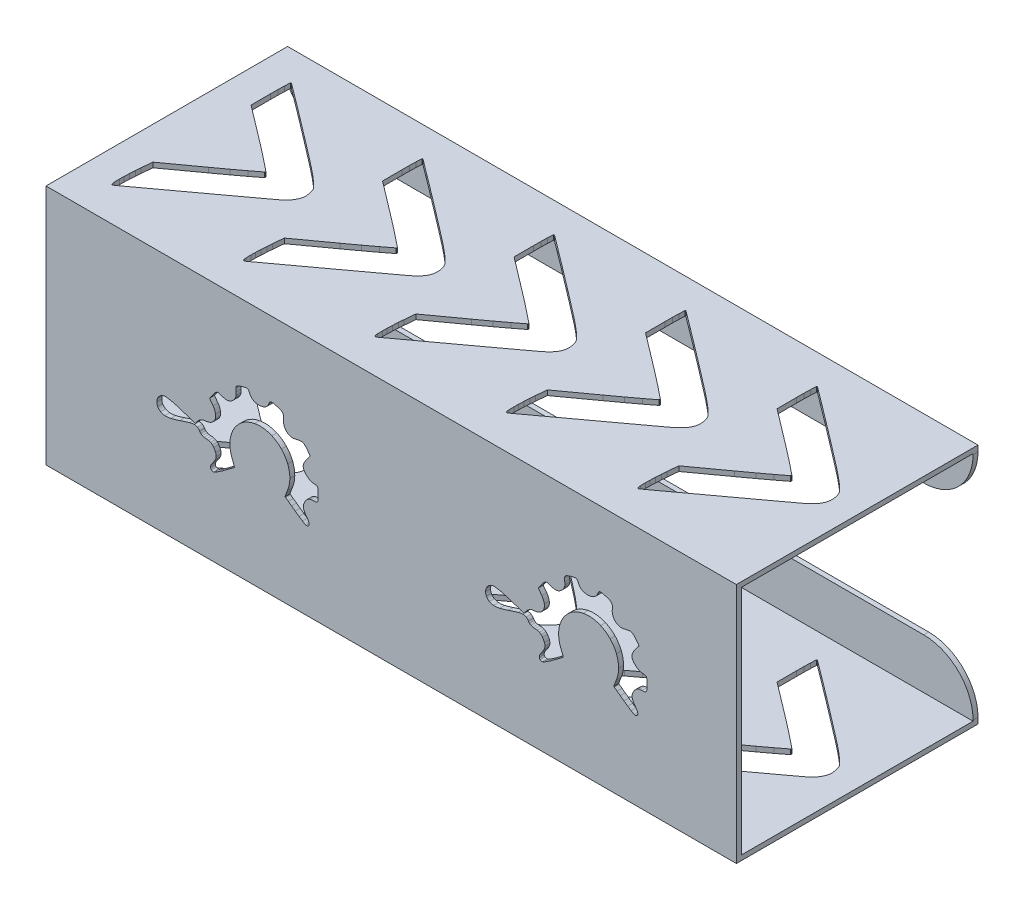
SolidWorks part; units mm, degrees
ref_plane "Front Plane" through (0, 0, 0) normal (1, 0, 0) x (0, 1, 0)
ref_plane "Top Plane" through (0, 0, 0) normal (0, 0, 1) x (0, 1, 0)
ref_plane "Right Plane" through (0, 0, 0) normal (0, 1, 0) x (-1, 0, 0)
sketch "Sketch1" plane through (0, 0, 0) normal (1, 0, 0) x (0, 1, 0)
  line L1 (0, 0) -> (73.5, 0)
  line L2 (0, 0) -> (0, -73.5)
  line L3 (0, -73.5) -> (73.5, -73.5)
  line L4 (73.5, 0) -> (73.5, -73.5)
  dimension "D1" = 73.5
  dimension "D2" = 73.5
extrude "Boss-Extrude1" add sketch "Sketch1" along normal blind 210
shell "Shell1" thickness 1.5
sketch "Sketch2" plane through (0, 0, -73.5) normal (0, 0, -1) x (1, 0, 0)
  line L0 (0, 0) -> (0, -73.5) construction
  line L1 (0, -16.75) -> (210, -16.75)
  line L2 (0, -16.75) -> (0, -56.75)
  line L3 (0, -56.75) -> (210, -56.75)
  line L4 (210, -16.75) -> (210, -56.75)
  line L5 (210, 0) -> (210, -73.5) construction
  line L6 (0, -36.75) -> (210, -36.75) construction
  dimension "D1" = 40
extrude "Cut-Extrude1" cut sketch "Sketch2" against normal up to surface (72 mm away) up to face at (105, 36.75, -1.5)
fillet "Fillet1" radius 15 4 edges at (0, 16.75, -72.75) (0, 56.75, -72.75) (210, 16.75, -72.75) (210, 56.75, -72.75)
sketch "Sketch3" plane through (0, 0, 0) normal (0, -1, 0) x (1, 0, 0)
  line L11 (9.6633, -19.2287) -> (9.9758, -22.537)
  line L12 (9.9758, -22.537) -> (19.7943, -29.6426)
  line L13 (19.7704, -44.9753) -> (9.8778, -52.4962)
  line L14 (9.8778, -52.4962) -> (9.8646, -58.4652)
  line L15 (10.3119, -64.3696) -> (14.8164, -60.9945)
  line L16 (21.2461, -18.6408) -> (10.7313, -10.9162)
  line L31 (49.6633, -19.2287) -> (49.9758, -22.537)
  line L32 (49.9758, -22.537) -> (59.7943, -29.6426)
  line L33 (59.7704, -44.9753) -> (49.8778, -52.4962)
  line L34 (49.8778, -52.4962) -> (49.8646, -58.4652)
  line L35 (50.3119, -64.3696) -> (54.8164, -60.9945)
  line L36 (61.2461, -18.6408) -> (50.7313, -10.9162)
  line L37 (89.6633, -19.2287) -> (89.9758, -22.537)
  line L38 (89.9758, -22.537) -> (99.7943, -29.6426)
  line L39 (99.7704, -44.9753) -> (89.8778, -52.4962)
  line L40 (89.8778, -52.4962) -> (89.8646, -58.4652)
  line L41 (90.3119, -64.3696) -> (94.8164, -60.9945)
  line L42 (101.2461, -18.6408) -> (90.7313, -10.9162)
  line L43 (129.6633, -19.2287) -> (129.9758, -22.537)
  line L44 (129.9758, -22.537) -> (139.7943, -29.6426)
  line L45 (139.7704, -44.9753) -> (129.8778, -52.4962)
  line L46 (129.8778, -52.4962) -> (129.8646, -58.4652)
  line L47 (130.3119, -64.3696) -> (134.8164, -60.9945)
  line L48 (141.2461, -18.6408) -> (130.7313, -10.9162)
  line L49 (169.6633, -19.2287) -> (169.9758, -22.537)
  line L50 (169.9758, -22.537) -> (179.7943, -29.6426)
  line L51 (179.7704, -44.9753) -> (169.8778, -52.4962)
  line L52 (169.8778, -52.4962) -> (169.8646, -58.4652)
  line L53 (170.3119, -64.3696) -> (174.8164, -60.9945)
  line L54 (181.2461, -18.6408) -> (170.7313, -10.9162)
  arc A69 (9.3471, -12.9692) -> (9.3707, -14.3369) centre (51.9904, -12.917) ccw
  arc A70 (9.3707, -14.3369) -> (9.4414, -16.0252) centre (107.7192, -11.0605) ccw
  arc A71 (9.4414, -16.0252) -> (9.5432, -17.7473) centre (110.2692, -10.9318) ccw
  arc A72 (9.5432, -17.7473) -> (9.6633, -19.2287) centre (65.2049, -13.9809) ccw
  arc A73 (23.5603, -32.3922) -> (19.7943, -29.6426) centre (-306.7468, -480.8529) ccw
  arc A74 (26.736, -34.7646) -> (23.5603, -32.3922) centre (-149.6013, -267.4951) ccw
  arc A75 (29.5168, -36.8768) -> (26.736, -34.7646) centre (-846.1457, -1186.7971) ccw
  arc A76 (29.6381, -37.1011) -> (29.5168, -36.8768) centre (29.3291, -37.1233) ccw
  arc A77 (29.5389, -37.3284) -> (29.6381, -37.1011) centre (29.3719, -37.1202) ccw
  arc A78 (26.75, -39.5597) -> (29.5389, -37.3284) centre (-850.317, 1059.5567) ccw
  arc A79 (23.5616, -42.0662) -> (26.75, -39.5597) centre (-147.1808, 178.4052) ccw
  arc A80 (19.7704, -44.9753) -> (23.5616, -42.0662) centre (-304.1542, 381.0974) ccw
  arc A81 (9.8646, -58.4652) -> (9.8787, -60.754) centre (146.6597, -58.7673) ccw
  arc A82 (9.8787, -60.754) -> (9.9336, -62.6808) centre (79.0341, -59.7495) ccw
  arc A83 (9.9336, -62.6808) -> (10.01, -64.3317) centre (222.492, -53.6638) ccw
  arc A84 (10.01, -64.3317) -> (10.1178, -64.4342) centre (10.1178, -64.3263) ccw
  arc A85 (10.1178, -64.4342) -> (10.3119, -64.3696) centre (10.1178, -64.1106) ccw
  arc A86 (14.8164, -60.9945) -> (19.8325, -57.2143) centre (-718.1391, 916.8002) ccw
  arc A87 (19.8325, -57.2143) -> (25.7388, -52.7247) centre (-1410.6569, 1830.8178) ccw
  arc A88 (25.7388, -52.7247) -> (34.2763, -46.1677) centre (-929.7355, 1200.1846) ccw
  arc A89 (34.2763, -46.1677) -> (38.4646, -42.775) centre (-39.0599, 48.6473) ccw
  arc A90 (38.4646, -42.775) -> (40.8424, -40.5892) centre (12.366, -11.9978) ccw
  arc A91 (40.8424, -40.5892) -> (41.7639, -39.1357) centre (38.0891, -37.8248) ccw
  arc A92 (41.7639, -39.1357) -> (42.1636, -37.0187) centre (35.2358, -36.8069) ccw
  arc A93 (42.1636, -37.0187) -> (41.8194, -35.0985) centre (37.4413, -36.8743) ccw
  arc A94 (41.8194, -35.0985) -> (40.6686, -33.2867) centre (36.2813, -37.3449) ccw
  arc A95 (40.6686, -33.2867) -> (38.6605, -31.4846) centre (29.9998, -43.1552) ccw
  arc A96 (38.6605, -31.4846) -> (31.0836, -25.8807) centre (-1705.4642, -2381.7586) ccw
  arc A97 (31.0836, -25.8807) -> (21.2461, -18.6408) centre (-4787.6013, -6563.1202) ccw
  arc A98 (10.7313, -10.9162) -> (9.9784, -10.4092) centre (4.1483, -19.8789) ccw
  arc A99 (9.9784, -10.4092) -> (9.6868, -10.4253) centre (9.8442, -10.6272) ccw
  arc A100 (9.6868, -10.4253) -> (9.4817, -10.7416) centre (10.0409, -10.8795) ccw
  arc A101 (9.4817, -10.7416) -> (9.3727, -11.5193) centre (13.2039, -11.6596) ccw
  arc A102 (9.3727, -11.5193) -> (9.3471, -12.9692) centre (47.6772, -12.9223) ccw
  arc A277 (63.5603, -32.3922) -> (59.7943, -29.6426) centre (-266.7468, -480.8529) ccw
  arc A278 (66.736, -34.7646) -> (63.5603, -32.3922) centre (-109.6013, -267.4951) ccw
  arc A279 (69.5168, -36.8768) -> (66.736, -34.7646) centre (-806.1457, -1186.7971) ccw
  arc A280 (69.6381, -37.1011) -> (69.5168, -36.8768) centre (69.3291, -37.1233) ccw
  arc A281 (69.5389, -37.3284) -> (69.6381, -37.1011) centre (69.3719, -37.1202) ccw
  arc A282 (66.75, -39.5597) -> (69.5389, -37.3284) centre (-810.317, 1059.5567) ccw
  arc A283 (63.5616, -42.0662) -> (66.75, -39.5597) centre (-107.1808, 178.4052) ccw
  arc A284 (59.7704, -44.9753) -> (63.5616, -42.0662) centre (-264.1542, 381.0974) ccw
  arc A285 (49.8646, -58.4652) -> (49.8787, -60.754) centre (186.6597, -58.7673) ccw
  arc A286 (49.8787, -60.754) -> (49.9336, -62.6808) centre (119.0341, -59.7495) ccw
  arc A287 (49.9336, -62.6808) -> (50.01, -64.3317) centre (262.492, -53.6638) ccw
  arc A288 (50.01, -64.3317) -> (50.1178, -64.4342) centre (50.1178, -64.3263) ccw
  arc A289 (50.1178, -64.4342) -> (50.3119, -64.3696) centre (50.1178, -64.1106) ccw
  arc A290 (54.8164, -60.9945) -> (59.8325, -57.2143) centre (-678.1391, 916.8002) ccw
  arc A291 (59.8325, -57.2143) -> (65.7388, -52.7247) centre (-1370.6569, 1830.8178) ccw
  arc A292 (65.7388, -52.7247) -> (74.2763, -46.1677) centre (-889.7355, 1200.1846) ccw
  arc A293 (74.2763, -46.1677) -> (78.4646, -42.775) centre (0.9401, 48.6473) ccw
  arc A294 (78.4646, -42.775) -> (80.8424, -40.5892) centre (52.366, -11.9978) ccw
  arc A295 (80.8424, -40.5892) -> (81.7639, -39.1357) centre (78.0891, -37.8248) ccw
  arc A296 (81.7639, -39.1357) -> (82.1636, -37.0187) centre (75.2358, -36.8069) ccw
  arc A297 (82.1636, -37.0187) -> (81.8194, -35.0985) centre (77.4413, -36.8743) ccw
  arc A298 (81.8194, -35.0985) -> (80.6686, -33.2867) centre (76.2813, -37.3449) ccw
  arc A299 (80.6686, -33.2867) -> (78.6605, -31.4846) centre (69.9998, -43.1552) ccw
  arc A300 (78.6605, -31.4846) -> (71.0836, -25.8807) centre (-1665.4642, -2381.7586) ccw
  arc A301 (71.0836, -25.8807) -> (61.2461, -18.6408) centre (-4747.6013, -6563.1202) ccw
  arc A302 (50.7313, -10.9162) -> (49.9784, -10.4092) centre (44.1483, -19.8789) ccw
  arc A303 (49.9784, -10.4092) -> (49.6868, -10.4253) centre (49.8442, -10.6272) ccw
  arc A304 (49.6868, -10.4253) -> (49.4817, -10.7416) centre (50.0409, -10.8795) ccw
  arc A305 (49.4817, -10.7416) -> (49.3727, -11.5193) centre (53.2039, -11.6596) ccw
  arc A306 (49.3727, -11.5193) -> (49.3471, -12.9692) centre (87.6772, -12.9223) ccw
  arc A307 (49.3471, -12.9692) -> (49.3707, -14.3369) centre (91.9904, -12.917) ccw
  arc A308 (49.3707, -14.3369) -> (49.4414, -16.0252) centre (147.7192, -11.0605) ccw
  arc A309 (49.4414, -16.0252) -> (49.5432, -17.7473) centre (150.2692, -10.9318) ccw
  arc A310 (49.5432, -17.7473) -> (49.6633, -19.2287) centre (105.2049, -13.9809) ccw
  arc A311 (103.5603, -32.3922) -> (99.7943, -29.6426) centre (-226.7468, -480.8529) ccw
  arc A312 (106.736, -34.7646) -> (103.5603, -32.3922) centre (-69.6013, -267.4951) ccw
  arc A313 (109.5168, -36.8768) -> (106.736, -34.7646) centre (-766.1457, -1186.7971) ccw
  arc A314 (109.6381, -37.1011) -> (109.5168, -36.8768) centre (109.3291, -37.1233) ccw
  arc A315 (109.5389, -37.3284) -> (109.6381, -37.1011) centre (109.3719, -37.1202) ccw
  arc A316 (106.75, -39.5597) -> (109.5389, -37.3284) centre (-770.317, 1059.5567) ccw
  arc A317 (103.5616, -42.0662) -> (106.75, -39.5597) centre (-67.1808, 178.4052) ccw
  arc A318 (99.7704, -44.9753) -> (103.5616, -42.0662) centre (-224.1542, 381.0974) ccw
  arc A319 (89.8646, -58.4652) -> (89.8787, -60.754) centre (226.6597, -58.7673) ccw
  arc A320 (89.8787, -60.754) -> (89.9336, -62.6808) centre (159.0341, -59.7495) ccw
  arc A321 (89.9336, -62.6808) -> (90.01, -64.3317) centre (302.492, -53.6638) ccw
  arc A322 (90.01, -64.3317) -> (90.1178, -64.4342) centre (90.1178, -64.3263) ccw
  arc A323 (90.1178, -64.4342) -> (90.3119, -64.3696) centre (90.1178, -64.1106) ccw
  arc A324 (94.8164, -60.9945) -> (99.8325, -57.2143) centre (-638.1391, 916.8002) ccw
  arc A325 (99.8325, -57.2143) -> (105.7388, -52.7247) centre (-1330.6569, 1830.8178) ccw
  arc A326 (105.7388, -52.7247) -> (114.2763, -46.1677) centre (-849.7355, 1200.1846) ccw
  arc A327 (114.2763, -46.1677) -> (118.4646, -42.775) centre (40.9401, 48.6473) ccw
  arc A328 (118.4646, -42.775) -> (120.8424, -40.5892) centre (92.366, -11.9978) ccw
  arc A329 (120.8424, -40.5892) -> (121.7639, -39.1357) centre (118.0891, -37.8248) ccw
  arc A330 (121.7639, -39.1357) -> (122.1636, -37.0187) centre (115.2358, -36.8069) ccw
  arc A331 (122.1636, -37.0187) -> (121.8194, -35.0985) centre (117.4413, -36.8743) ccw
  arc A332 (121.8194, -35.0985) -> (120.6686, -33.2867) centre (116.2813, -37.3449) ccw
  arc A333 (120.6686, -33.2867) -> (118.6605, -31.4846) centre (109.9998, -43.1552) ccw
  arc A334 (118.6605, -31.4846) -> (111.0836, -25.8807) centre (-1625.4642, -2381.7586) ccw
  arc A335 (111.0836, -25.8807) -> (101.2461, -18.6408) centre (-4707.6013, -6563.1202) ccw
  arc A336 (90.7313, -10.9162) -> (89.9784, -10.4092) centre (84.1483, -19.8789) ccw
  arc A337 (89.9784, -10.4092) -> (89.6868, -10.4253) centre (89.8442, -10.6272) ccw
  arc A338 (89.6868, -10.4253) -> (89.4817, -10.7416) centre (90.0409, -10.8795) ccw
  arc A339 (89.4817, -10.7416) -> (89.3727, -11.5193) centre (93.2039, -11.6596) ccw
  arc A340 (89.3727, -11.5193) -> (89.3471, -12.9692) centre (127.6772, -12.9223) ccw
  arc A341 (89.3471, -12.9692) -> (89.3707, -14.3369) centre (131.9904, -12.917) ccw
  arc A342 (89.3707, -14.3369) -> (89.4414, -16.0252) centre (187.7192, -11.0605) ccw
  arc A343 (89.4414, -16.0252) -> (89.5432, -17.7473) centre (190.2692, -10.9318) ccw
  arc A344 (89.5432, -17.7473) -> (89.6633, -19.2287) centre (145.2049, -13.9809) ccw
  arc A345 (143.5603, -32.3922) -> (139.7943, -29.6426) centre (-186.7468, -480.8529) ccw
  arc A346 (146.736, -34.7646) -> (143.5603, -32.3922) centre (-29.6013, -267.4951) ccw
  arc A347 (149.5168, -36.8768) -> (146.736, -34.7646) centre (-726.1457, -1186.7971) ccw
  arc A348 (149.6381, -37.1011) -> (149.5168, -36.8768) centre (149.3291, -37.1233) ccw
  arc A349 (149.5389, -37.3284) -> (149.6381, -37.1011) centre (149.3719, -37.1202) ccw
  arc A350 (146.75, -39.5597) -> (149.5389, -37.3284) centre (-730.317, 1059.5567) ccw
  arc A351 (143.5616, -42.0662) -> (146.75, -39.5597) centre (-27.1808, 178.4052) ccw
  arc A352 (139.7704, -44.9753) -> (143.5616, -42.0662) centre (-184.1542, 381.0974) ccw
  arc A353 (129.8646, -58.4652) -> (129.8787, -60.754) centre (266.6597, -58.7673) ccw
  arc A354 (129.8787, -60.754) -> (129.9336, -62.6808) centre (199.0341, -59.7495) ccw
  arc A355 (129.9336, -62.6808) -> (130.01, -64.3317) centre (342.492, -53.6638) ccw
  arc A356 (130.01, -64.3317) -> (130.1178, -64.4342) centre (130.1178, -64.3263) ccw
  arc A357 (130.1178, -64.4342) -> (130.3119, -64.3696) centre (130.1178, -64.1106) ccw
  arc A358 (134.8164, -60.9945) -> (139.8325, -57.2143) centre (-598.1391, 916.8002) ccw
  arc A359 (139.8325, -57.2143) -> (145.7388, -52.7247) centre (-1290.6569, 1830.8178) ccw
  arc A360 (145.7388, -52.7247) -> (154.2763, -46.1677) centre (-809.7355, 1200.1846) ccw
  arc A361 (154.2763, -46.1677) -> (158.4646, -42.775) centre (80.9401, 48.6473) ccw
  arc A362 (158.4646, -42.775) -> (160.8424, -40.5892) centre (132.366, -11.9978) ccw
  arc A363 (160.8424, -40.5892) -> (161.7639, -39.1357) centre (158.0891, -37.8248) ccw
  arc A364 (161.7639, -39.1357) -> (162.1636, -37.0187) centre (155.2358, -36.8069) ccw
  arc A365 (162.1636, -37.0187) -> (161.8194, -35.0985) centre (157.4413, -36.8743) ccw
  arc A366 (161.8194, -35.0985) -> (160.6686, -33.2867) centre (156.2813, -37.3449) ccw
  arc A367 (160.6686, -33.2867) -> (158.6605, -31.4846) centre (149.9998, -43.1552) ccw
  arc A368 (158.6605, -31.4846) -> (151.0836, -25.8807) centre (-1585.4642, -2381.7586) ccw
  arc A369 (151.0836, -25.8807) -> (141.2461, -18.6408) centre (-4667.6013, -6563.1202) ccw
  arc A370 (130.7313, -10.9162) -> (129.9784, -10.4092) centre (124.1483, -19.8789) ccw
  arc A371 (129.9784, -10.4092) -> (129.6868, -10.4253) centre (129.8442, -10.6272) ccw
  arc A372 (129.6868, -10.4253) -> (129.4817, -10.7416) centre (130.0409, -10.8795) ccw
  arc A373 (129.4817, -10.7416) -> (129.3727, -11.5193) centre (133.2039, -11.6596) ccw
  arc A374 (129.3727, -11.5193) -> (129.3471, -12.9692) centre (167.6772, -12.9223) ccw
  arc A375 (129.3471, -12.9692) -> (129.3707, -14.3369) centre (171.9904, -12.917) ccw
  arc A376 (129.3707, -14.3369) -> (129.4414, -16.0252) centre (227.7192, -11.0605) ccw
  arc A377 (129.4414, -16.0252) -> (129.5432, -17.7473) centre (230.2692, -10.9318) ccw
  arc A378 (129.5432, -17.7473) -> (129.6633, -19.2287) centre (185.2049, -13.9809) ccw
  arc A379 (183.5603, -32.3922) -> (179.7943, -29.6426) centre (-146.7468, -480.8529) ccw
  arc A380 (186.736, -34.7646) -> (183.5603, -32.3922) centre (10.3987, -267.4951) ccw
  arc A381 (189.5168, -36.8768) -> (186.736, -34.7646) centre (-686.1457, -1186.7971) ccw
  arc A382 (189.6381, -37.1011) -> (189.5168, -36.8768) centre (189.3291, -37.1233) ccw
  arc A383 (189.5389, -37.3284) -> (189.6381, -37.1011) centre (189.3719, -37.1202) ccw
  arc A384 (186.75, -39.5597) -> (189.5389, -37.3284) centre (-690.317, 1059.5567) ccw
  arc A385 (183.5616, -42.0662) -> (186.75, -39.5597) centre (12.8192, 178.4052) ccw
  arc A386 (179.7704, -44.9753) -> (183.5616, -42.0662) centre (-144.1542, 381.0974) ccw
  arc A387 (169.8646, -58.4652) -> (169.8787, -60.754) centre (306.6597, -58.7673) ccw
  arc A388 (169.8787, -60.754) -> (169.9336, -62.6808) centre (239.0341, -59.7495) ccw
  arc A389 (169.9336, -62.6808) -> (170.01, -64.3317) centre (382.492, -53.6638) ccw
  arc A390 (170.01, -64.3317) -> (170.1178, -64.4342) centre (170.1178, -64.3263) ccw
  arc A391 (170.1178, -64.4342) -> (170.3119, -64.3696) centre (170.1178, -64.1106) ccw
  arc A392 (174.8164, -60.9945) -> (179.8325, -57.2143) centre (-558.1391, 916.8002) ccw
  arc A393 (179.8325, -57.2143) -> (185.7388, -52.7247) centre (-1250.6569, 1830.8178) ccw
  arc A394 (185.7388, -52.7247) -> (194.2763, -46.1677) centre (-769.7355, 1200.1846) ccw
  arc A395 (194.2763, -46.1677) -> (198.4646, -42.775) centre (120.9401, 48.6473) ccw
  arc A396 (198.4646, -42.775) -> (200.8424, -40.5892) centre (172.366, -11.9978) ccw
  arc A397 (200.8424, -40.5892) -> (201.7639, -39.1357) centre (198.0891, -37.8248) ccw
  arc A398 (201.7639, -39.1357) -> (202.1636, -37.0187) centre (195.2358, -36.8069) ccw
  arc A399 (202.1636, -37.0187) -> (201.8194, -35.0985) centre (197.4413, -36.8743) ccw
  arc A400 (201.8194, -35.0985) -> (200.6686, -33.2867) centre (196.2813, -37.3449) ccw
  arc A401 (200.6686, -33.2867) -> (198.6605, -31.4846) centre (189.9998, -43.1552) ccw
  arc A402 (198.6605, -31.4846) -> (191.0836, -25.8807) centre (-1545.4642, -2381.7586) ccw
  arc A403 (191.0836, -25.8807) -> (181.2461, -18.6408) centre (-4627.6013, -6563.1202) ccw
  arc A404 (170.7313, -10.9162) -> (169.9784, -10.4092) centre (164.1483, -19.8789) ccw
  arc A405 (169.9784, -10.4092) -> (169.6868, -10.4253) centre (169.8442, -10.6272) ccw
  arc A406 (169.6868, -10.4253) -> (169.4817, -10.7416) centre (170.0409, -10.8795) ccw
  arc A407 (169.4817, -10.7416) -> (169.3727, -11.5193) centre (173.2039, -11.6596) ccw
  arc A408 (169.3727, -11.5193) -> (169.3471, -12.9692) centre (207.6772, -12.9223) ccw
  arc A409 (169.3471, -12.9692) -> (169.3707, -14.3369) centre (211.9904, -12.917) ccw
  arc A410 (169.3707, -14.3369) -> (169.4414, -16.0252) centre (267.7192, -11.0605) ccw
  arc A411 (169.4414, -16.0252) -> (169.5432, -17.7473) centre (270.2692, -10.9318) ccw
  arc A412 (169.5432, -17.7473) -> (169.6633, -19.2287) centre (225.2049, -13.9809) ccw
  dimension "D1" = 5
extrude "Cut-Extrude2" cut sketch "Sketch3" against normal through all
sketch "Sketch7" plane through (0, 0, 0) normal (0, 0, 1) x (-1, 0, 0)
  line L55 (-179.3217, -41.1409) -> (-180.4065, -42.52)
  line L56 (-180.4065, -42.52) -> (-179.3772, -43.8764)
  line L57 (-150.8373, -44.0084) -> (-149.7387, -42.4655)
  line L58 (-149.7387, -42.4655) -> (-150.8112, -41.0148)
  line L59 (-146.277, -34.7471) -> (-145.3963, -33.6595)
  line L60 (-145.3963, -33.6595) -> (-141.2197, -35.0505)
  line L61 (-154.3079, -25.7512) -> (-155.4129, -26.5732)
  line L62 (-155.4129, -26.5732) -> (-156.3598, -27.2767)
  line L63 (-156.3598, -27.2767) -> (-157.1862, -27.8902)
  line L64 (-172.8725, -27.8886) -> (-173.7152, -27.2751)
  line L65 (-173.7152, -27.2751) -> (-174.6812, -26.5717)
  line L66 (-174.6812, -26.5717) -> (-175.8021, -25.7552)
  line L67 (-79.3217, -41.1409) -> (-80.4065, -42.52)
  line L68 (-80.4065, -42.52) -> (-79.3772, -43.8764)
  line L69 (-50.8373, -44.0084) -> (-49.7387, -42.4655)
  line L70 (-49.7387, -42.4655) -> (-50.8112, -41.0148)
  line L71 (-46.277, -34.7471) -> (-45.3963, -33.6595)
  line L72 (-45.3963, -33.6595) -> (-41.2197, -35.0505)
  line L73 (-54.3079, -25.7512) -> (-55.4129, -26.5732)
  line L74 (-55.4129, -26.5732) -> (-56.3598, -27.2767)
  line L75 (-56.3598, -27.2767) -> (-57.1862, -27.8902)
  line L76 (-72.8725, -27.8886) -> (-73.7152, -27.2751)
  line L77 (-73.7152, -27.2751) -> (-74.6812, -26.5717)
  line L78 (-74.6812, -26.5717) -> (-75.8021, -25.7552)
  arc A413 (-180.4257, -36.0856) -> (-181.5388, -35.8347) centre (-181.5388, -38.4304) ccw
  arc A414 (-179.3274, -36.8188) -> (-180.4257, -36.0856) centre (-182.3795, -40.2013) ccw
  arc A415 (-178.5138, -37.8098) -> (-179.3274, -36.8188) centre (-182.215, -40.0189) ccw
  arc A416 (-178.2368, -38.8142) -> (-178.5138, -37.8098) centre (-180.1966, -38.8142) ccw
  arc A417 (-178.3109, -39.2731) -> (-178.2368, -38.8142) centre (-179.6946, -38.8142) ccw
  arc A418 (-178.5555, -39.8885) -> (-178.3109, -39.2731) centre (-183.7292, -37.4762) ccw
  arc A419 (-178.9065, -40.5433) -> (-178.5555, -39.8885) centre (-184.5938, -37.0731) ccw
  arc A420 (-179.3217, -41.1409) -> (-178.9065, -40.5433) centre (-184.1447, -37.3471) ccw
  arc A421 (-179.3772, -43.8764) -> (-178.6531, -44.693) centre (-173.6749, -39.5492) ccw
  arc A422 (-178.6531, -44.693) -> (-178.0494, -45.016) centre (-177.785, -43.7959) ccw
  arc A423 (-178.0494, -45.016) -> (-177.2478, -45.0303) centre (-177.6125, -43.0006) ccw
  arc A424 (-177.2478, -45.0303) -> (-175.6195, -44.691) centre (-182.5834, -15.3439) ccw
  arc A425 (-174.2898, -44.7381) -> (-175.6195, -44.691) centre (-175.0402, -47.1324) ccw
  arc A426 (-173.1167, -45.455) -> (-174.2898, -44.7381) centre (-175.138, -47.4442) ccw
  arc A427 (-172.379, -46.6738) -> (-173.1167, -45.455) centre (-175.3138, -47.6173) ccw
  arc A428 (-172.2605, -48.1041) -> (-172.379, -46.6738) centre (-175.3964, -47.6439) ccw
  arc A429 (-172.2605, -48.1041) -> (-172.2619, -49.1259) centre (-168.7481, -48.6196) ccw
  arc A430 (-172.2619, -49.1259) -> (-171.9159, -49.8005) centre (-171.1069, -48.9595) ccw
  arc A431 (-171.9159, -49.8005) -> (-171.1097, -50.2905) centre (-170.4165, -48.2418) ccw
  arc A432 (-171.1097, -50.2905) -> (-169.5084, -50.7515) centre (-165.2962, -33.1087) ccw
  arc A433 (-169.5084, -50.7515) -> (-168.7977, -50.8707) centre (-168.2786, -45.6007) ccw
  arc A434 (-168.7977, -50.8707) -> (-168.3518, -50.8022) centre (-168.7086, -49.9654) ccw
  arc A435 (-168.3518, -50.8022) -> (-168.0469, -50.5394) centre (-168.6118, -50.1925) ccw
  arc A436 (-168.0469, -50.5394) -> (-167.8133, -50.0288) centre (-170.0166, -49.3295) ccw
  arc A437 (-166.7743, -48.703) -> (-167.8133, -50.0288) centre (-165.5186, -50.7571) ccw
  arc A438 (-164.9464, -48.1479) -> (-166.7743, -48.703) centre (-164.7908, -51.9476) ccw
  arc A439 (-163.0945, -48.5539) -> (-164.9464, -48.1479) centre (-164.7937, -51.878) ccw
  arc A440 (-161.9863, -49.7902) -> (-163.0945, -48.5539) centre (-164.1462, -50.6114) ccw
  arc A441 (-161.9863, -49.7902) -> (-161.6713, -50.4494) centre (-157.8447, -48.2156) ccw
  arc A442 (-161.6713, -50.4494) -> (-161.3391, -50.7344) centre (-161.0936, -50.1121) ccw
  arc A443 (-161.3391, -50.7344) -> (-160.8627, -50.7816) centre (-161.0178, -49.92) ccw
  arc A444 (-160.8627, -50.7816) -> (-159.9889, -50.5782) centre (-162.4341, -42.0521) ccw
  arc A445 (-159.9889, -50.5782) -> (-158.5462, -50.1113) centre (-166.1882, -28.9623) ccw
  arc A446 (-158.5462, -50.1113) -> (-157.9553, -49.7098) centre (-159.0368, -48.7538) ccw
  arc A447 (-157.9553, -49.7098) -> (-157.7327, -49.1396) centre (-158.6211, -49.1212) ccw
  arc A448 (-157.7327, -49.1396) -> (-157.7978, -48.0994) centre (-164.0024, -49.01) ccw
  arc A449 (-157.8333, -47.3478) -> (-157.7978, -48.0994) centre (-154.0114, -47.5437) ccw
  arc A450 (-157.7066, -46.6918) -> (-157.8333, -47.3478) centre (-155.437, -47.4706) ccw
  arc A451 (-157.4011, -46.0867) -> (-157.7066, -46.6918) centre (-155.3587, -47.4975) ccw
  arc A452 (-156.9014, -45.4873) -> (-157.4011, -46.0867) centre (-153.847, -48.5417) ccw
  arc A453 (-156.0692, -44.8679) -> (-156.9014, -45.4873) centre (-154.3732, -48.0155) ccw
  arc A454 (-155.1947, -44.6147) -> (-156.0692, -44.8679) centre (-155.0448, -46.7691) ccw
  arc A455 (-154.1488, -44.7194) -> (-155.1947, -44.6147) centre (-154.9781, -47.7269) ccw
  arc A456 (-152.7674, -45.1997) -> (-154.1488, -44.7194) centre (-157.1187, -55.4896) ccw
  arc A457 (-152.7674, -45.1997) -> (-152.3251, -45.2609) centre (-152.4323, -44.4073) ccw
  arc A458 (-152.3251, -45.2609) -> (-151.8725, -45.1013) centre (-152.4659, -44.1399) ccw
  arc A459 (-151.8725, -45.1013) -> (-151.3863, -44.6946) centre (-153.0359, -43.2165) ccw
  arc A460 (-151.3863, -44.6946) -> (-150.8373, -44.0084) centre (-157.24, -39.4493) ccw
  arc A461 (-151.5774, -39.2295) -> (-150.8112, -41.0148) centre (-147.4025, -38.4947) ccw
  arc A462 (-151.3315, -37.5125) -> (-151.5774, -39.2295) centre (-148.8331, -38.7465) ccw
  arc A463 (-150.1213, -36.285) -> (-151.3315, -37.5125) centre (-148.8717, -38.7274) ccw
  arc A464 (-148.2526, -35.8347) -> (-150.1213, -36.285) centre (-148.2526, -39.9373) ccw
  arc A465 (-148.2526, -35.8347) -> (-147.7692, -35.7559) centre (-148.2526, -34.3137) ccw
  arc A466 (-147.7692, -35.7559) -> (-147.2206, -35.5153) centre (-148.8296, -32.5924) ccw
  arc A467 (-147.2206, -35.5153) -> (-146.6949, -35.1633) centre (-148.983, -32.3138) ccw
  arc A468 (-146.6949, -35.1633) -> (-146.277, -34.7471) centre (-148.4272, -33.006) ccw
  arc A469 (-141.2197, -35.0505) -> (-139.4009, -35.6076) centre (-128.8343, 2.1394) ccw
  arc A470 (-139.4009, -35.6076) -> (-137.8243, -35.9831) centre (-133.808, -15.6282) ccw
  arc A471 (-137.8243, -35.9831) -> (-136.553, -36.1774) centre (-134.9422, -21.3766) ccw
  arc A472 (-136.553, -36.1774) -> (-135.7787, -36.1241) centre (-136.3147, -33.9882) ccw
  arc A473 (-135.7787, -36.1241) -> (-134.7274, -35.588) centre (-136.4206, -33.5666) ccw
  arc A474 (-134.7274, -35.588) -> (-133.9847, -34.6356) centre (-136.5773, -33.3795) ccw
  arc A475 (-133.9847, -34.6356) -> (-133.7118, -33.4879) centre (-136.4423, -33.4449) ccw
  arc A476 (-133.7118, -33.4879) -> (-133.9752, -32.4014) centre (-135.9396, -33.4528) ccw
  arc A477 (-133.9752, -32.4014) -> (-134.8598, -31.477) centre (-136.0749, -33.5252) ccw
  arc A478 (-134.8598, -31.477) -> (-136.1395, -31.0877) centre (-136.2945, -33.8954) ccw
  arc A479 (-136.1395, -31.0877) -> (-137.9879, -31.2557) centre (-136.4917, -37.4658) ccw
  arc A480 (-137.9879, -31.2557) -> (-140.6662, -32.032) centre (-130.841, -60.9193) ccw
  arc A481 (-143.6014, -32.9683) -> (-140.6662, -32.032) centre (-166.6963, 44.4995) ccw
  arc A482 (-145.1237, -33.2221) -> (-143.6014, -32.9683) centre (-145.3757, -27.0167) ccw
  arc A483 (-146.0607, -32.9871) -> (-145.1237, -33.2221) centre (-145.1931, -31.5133) ccw
  arc A484 (-146.7408, -32.2787) -> (-146.0607, -32.9871) centre (-145.1391, -31.4215) ccw
  arc A485 (-146.7408, -32.2787) -> (-147.0704, -31.8445) centre (-148.2704, -33.0974) ccw
  arc A486 (-147.0704, -31.8445) -> (-147.5245, -31.5238) centre (-148.3653, -33.1964) ccw
  arc A487 (-147.5245, -31.5238) -> (-148.0938, -31.3283) centre (-148.5285, -33.5212) ccw
  arc A488 (-148.0938, -31.3283) -> (-148.7619, -31.2627) centre (-148.7619, -34.698) ccw
  arc A489 (-149.443, -31.1889) -> (-148.7619, -31.2627) centre (-148.7619, -28.0869) ccw
  arc A490 (-150.0616, -30.9707) -> (-149.443, -31.1889) centre (-148.869, -28.5749) ccw
  arc A491 (-150.5963, -30.6145) -> (-150.0616, -30.9707) centre (-148.9217, -28.6807) ccw
  arc A492 (-151.03, -30.1337) -> (-150.5963, -30.6145) centre (-148.8695, -28.6204) ccw
  arc A493 (-151.614, -29.0568) -> (-151.03, -30.1337) centre (-146.624, -27.0476) ccw
  arc A494 (-151.7688, -28.0984) -> (-151.614, -29.0568) centre (-149.5742, -28.2355) ccw
  arc A495 (-151.4982, -27.1265) -> (-151.7688, -28.0984) centre (-149.3442, -28.2499) ccw
  arc A496 (-150.7718, -26.0022) -> (-151.4982, -27.1265) centre (-145.1006, -30.4631) ccw
  arc A497 (-150.7718, -26.0022) -> (-150.1964, -25.0917) centre (-154.8924, -22.7609) ccw
  arc A498 (-150.1964, -25.0917) -> (-150.0425, -24.3322) centre (-151.5425, -24.4236) ccw
  arc A499 (-150.0425, -24.3322) -> (-150.3109, -23.8405) centre (-150.7004, -24.3723) ccw
  arc A500 (-150.3109, -23.8405) -> (-150.9156, -23.6427) centre (-150.9156, -24.6661) ccw
  arc A501 (-150.9156, -23.6427) -> (-151.2597, -23.7345) centre (-150.9156, -24.3335) ccw
  arc A502 (-151.2597, -23.7345) -> (-152.1446, -24.2636) centre (-136.5488, -49.3448) ccw
  arc A503 (-152.1446, -24.2636) -> (-153.186, -24.9467) centre (-138.574, -46.0878) ccw
  arc A504 (-153.186, -24.9467) -> (-154.3079, -25.7512) centre (-130.6122, -57.6073) ccw
  arc A505 (-157.2885, -27.9643) -> (-157.1862, -27.8902) centre (-160.4083, -23.549) ccw
  arc A506 (-157.2885, -27.9643) -> (-157.3198, -28.0554) centre (-157.2409, -28.0316) ccw
  arc A507 (-157.3198, -28.0554) -> (-157.1571, -28.5714) centre (-135.3012, -21.3959) ccw
  arc A508 (-157.1571, -28.5714) -> (-156.9385, -29.1864) centre (-144.3788, -24.3761) ccw
  arc A509 (-156.9385, -29.1864) -> (-156.6535, -29.8984) centre (-133.0805, -20.049) ccw
  arc A510 (-156.1101, -35.2903) -> (-156.6535, -29.8984) centre (-165.2433, -33.4875) ccw
  arc A511 (-158.6575, -40.0916) -> (-156.1101, -35.2903) centre (-165.3437, -33.4677) ccw
  arc A512 (-163.398, -42.6364) -> (-158.6575, -40.0916) centre (-165.1792, -33.6306) ccw
  arc A513 (-168.6907, -42.0486) -> (-163.398, -42.6364) centre (-165.1136, -33.962) ccw
  arc A514 (-171.5993, -40.0109) -> (-168.6907, -42.0486) centre (-164.9768, -33.6526) ccw
  arc A515 (-173.5226, -37.0187) -> (-171.5993, -40.0109) centre (-164.9367, -33.6141) ccw
  arc A516 (-174.1746, -33.5171) -> (-173.5226, -37.0187) centre (-164.9102, -33.6036) ccw
  arc A517 (-173.4578, -30.0268) -> (-174.1746, -33.5171) centre (-164.8968, -33.6038) ccw
  arc A518 (-173.4578, -30.0268) -> (-173.1522, -29.2654) centre (-200.3598, -18.7864) ccw
  arc A519 (-173.1522, -29.2654) -> (-172.9163, -28.6088) centre (-187.4446, -23.7607) ccw
  arc A520 (-172.9163, -28.6088) -> (-172.7381, -28.0556) centre (-199.3716, -19.7807) ccw
  arc A521 (-172.7381, -28.0556) -> (-172.7691, -27.9632) centre (-172.8176, -28.0309) ccw
  arc A522 (-172.8725, -27.8886) -> (-172.7691, -27.9632) centre (-163.9954, -15.694) ccw
  arc A523 (-175.8021, -25.7552) -> (-176.9492, -24.9459) centre (-202.9107, -62.9619) ccw
  arc A524 (-176.9492, -24.9459) -> (-177.9966, -24.2633) centre (-193.3079, -48.9003) ccw
  arc A525 (-177.9966, -24.2633) -> (-178.8866, -23.7277) centre (-197.118, -55.0309) ccw
  arc A526 (-178.8866, -23.7277) -> (-179.2011, -23.6427) centre (-179.2011, -24.2678) ccw
  arc A527 (-179.2011, -23.6427) -> (-179.7692, -23.8455) centre (-179.2011, -24.54) ccw
  arc A528 (-179.7692, -23.8455) -> (-180.0158, -24.3425) centre (-179.3429, -24.3666) ccw
  arc A529 (-180.0158, -24.3425) -> (-179.8518, -25.1053) centre (-178.4252, -24.3996) ccw
  arc A530 (-179.8518, -25.1053) -> (-179.2858, -26.0022) centre (-175.2544, -22.8311) ccw
  arc A531 (-178.5594, -27.1265) -> (-179.2858, -26.0022) centre (-184.957, -30.4631) ccw
  arc A532 (-178.2888, -28.0984) -> (-178.5594, -27.1265) centre (-180.7135, -28.2499) ccw
  arc A533 (-178.4436, -29.0568) -> (-178.2888, -28.0984) centre (-180.4834, -28.2355) ccw
  arc A534 (-179.0276, -30.1337) -> (-178.4436, -29.0568) centre (-183.4336, -27.0476) ccw
  arc A535 (-179.4636, -30.6169) -> (-179.0276, -30.1337) centre (-181.1985, -28.6132) ccw
  arc A536 (-179.9994, -30.9727) -> (-179.4636, -30.6169) centre (-181.1199, -28.7039) ccw
  arc A537 (-180.622, -31.1894) -> (-179.9994, -30.9727) centre (-181.182, -28.5783) ccw
  arc A538 (-181.3136, -31.2627) -> (-180.622, -31.1894) centre (-181.3136, -27.9644) ccw
  arc A539 (-181.3136, -31.2627) -> (-182.2055, -31.3308) centre (-181.3136, -37.1429) ccw
  arc A540 (-182.2055, -31.3308) -> (-182.5988, -31.5839) centre (-182.1184, -31.8981) ccw
  arc A541 (-182.5988, -31.5839) -> (-182.7741, -32.1238) centre (-181.6926, -32.1766) ccw
  arc A542 (-182.7741, -32.1238) -> (-182.8088, -33.5487) centre (-153.57, -33.5488) ccw
  arc A543 (-182.8088, -33.5487) -> (-182.7742, -34.9101) centre (-155.9949, -33.5488) ccw
  arc A544 (-182.7742, -34.9101) -> (-182.6113, -35.4791) centre (-181.4675, -34.8437) ccw
  arc A545 (-182.6113, -35.4791) -> (-182.2535, -35.7506) centre (-182.124, -35.2084) ccw
  arc A546 (-182.2535, -35.7506) -> (-181.5388, -35.8347) centre (-181.5388, -32.7576) ccw
  arc A547 (-79.3772, -43.8764) -> (-78.6531, -44.693) centre (-73.6749, -39.5492) ccw
  arc A548 (-78.6531, -44.693) -> (-78.0494, -45.016) centre (-77.785, -43.7959) ccw
  arc A549 (-78.0494, -45.016) -> (-77.2478, -45.0303) centre (-77.6125, -43.0006) ccw
  arc A550 (-77.2478, -45.0303) -> (-75.6195, -44.691) centre (-82.5834, -15.3439) ccw
  arc A551 (-74.2898, -44.7381) -> (-75.6195, -44.691) centre (-75.0402, -47.1324) ccw
  arc A552 (-73.1167, -45.455) -> (-74.2898, -44.7381) centre (-75.138, -47.4442) ccw
  arc A553 (-72.379, -46.6738) -> (-73.1167, -45.455) centre (-75.3138, -47.6173) ccw
  arc A554 (-72.2605, -48.1041) -> (-72.379, -46.6738) centre (-75.3964, -47.6439) ccw
  arc A555 (-72.2605, -48.1041) -> (-72.2619, -49.1259) centre (-68.7481, -48.6196) ccw
  arc A556 (-72.2619, -49.1259) -> (-71.9159, -49.8005) centre (-71.1069, -48.9595) ccw
  arc A557 (-71.9159, -49.8005) -> (-71.1097, -50.2905) centre (-70.4165, -48.2418) ccw
  arc A558 (-71.1097, -50.2905) -> (-69.5084, -50.7515) centre (-65.2962, -33.1087) ccw
  arc A559 (-69.5084, -50.7515) -> (-68.7977, -50.8707) centre (-68.2786, -45.6007) ccw
  arc A560 (-68.7977, -50.8707) -> (-68.3518, -50.8022) centre (-68.7086, -49.9654) ccw
  arc A561 (-68.3518, -50.8022) -> (-68.0469, -50.5394) centre (-68.6118, -50.1925) ccw
  arc A562 (-68.0469, -50.5394) -> (-67.8133, -50.0288) centre (-70.0166, -49.3295) ccw
  arc A563 (-66.7743, -48.703) -> (-67.8133, -50.0288) centre (-65.5186, -50.7571) ccw
  arc A564 (-64.9464, -48.1479) -> (-66.7743, -48.703) centre (-64.7908, -51.9476) ccw
  arc A565 (-63.0945, -48.5539) -> (-64.9464, -48.1479) centre (-64.7937, -51.878) ccw
  arc A566 (-61.9863, -49.7902) -> (-63.0945, -48.5539) centre (-64.1462, -50.6114) ccw
  arc A567 (-61.9863, -49.7902) -> (-61.6713, -50.4494) centre (-57.8447, -48.2156) ccw
  arc A568 (-61.6713, -50.4494) -> (-61.3391, -50.7344) centre (-61.0936, -50.1121) ccw
  arc A569 (-61.3391, -50.7344) -> (-60.8627, -50.7816) centre (-61.0178, -49.92) ccw
  arc A570 (-60.8627, -50.7816) -> (-59.9889, -50.5782) centre (-62.4341, -42.0521) ccw
  arc A571 (-59.9889, -50.5782) -> (-58.5462, -50.1113) centre (-66.1882, -28.9623) ccw
  arc A572 (-58.5462, -50.1113) -> (-57.9553, -49.7098) centre (-59.0368, -48.7538) ccw
  arc A573 (-57.9553, -49.7098) -> (-57.7327, -49.1396) centre (-58.6211, -49.1212) ccw
  arc A574 (-57.7327, -49.1396) -> (-57.7978, -48.0994) centre (-64.0024, -49.01) ccw
  arc A575 (-57.8333, -47.3478) -> (-57.7978, -48.0994) centre (-54.0114, -47.5437) ccw
  arc A576 (-57.7066, -46.6918) -> (-57.8333, -47.3478) centre (-55.437, -47.4706) ccw
  arc A577 (-57.4011, -46.0867) -> (-57.7066, -46.6918) centre (-55.3587, -47.4975) ccw
  arc A578 (-56.9014, -45.4873) -> (-57.4011, -46.0867) centre (-53.847, -48.5417) ccw
  arc A579 (-56.0692, -44.8679) -> (-56.9014, -45.4873) centre (-54.3732, -48.0155) ccw
  arc A580 (-55.1947, -44.6147) -> (-56.0692, -44.8679) centre (-55.0448, -46.7691) ccw
  arc A581 (-54.1488, -44.7194) -> (-55.1947, -44.6147) centre (-54.9781, -47.7269) ccw
  arc A582 (-52.7674, -45.1997) -> (-54.1488, -44.7194) centre (-57.1187, -55.4896) ccw
  arc A583 (-52.7674, -45.1997) -> (-52.3251, -45.2609) centre (-52.4323, -44.4073) ccw
  arc A584 (-52.3251, -45.2609) -> (-51.8725, -45.1013) centre (-52.4659, -44.1399) ccw
  arc A585 (-51.8725, -45.1013) -> (-51.3863, -44.6946) centre (-53.0359, -43.2165) ccw
  arc A586 (-51.3863, -44.6946) -> (-50.8373, -44.0084) centre (-57.24, -39.4493) ccw
  arc A587 (-51.5774, -39.2295) -> (-50.8112, -41.0148) centre (-47.4025, -38.4947) ccw
  arc A588 (-51.3315, -37.5125) -> (-51.5774, -39.2295) centre (-48.8331, -38.7465) ccw
  arc A589 (-50.1213, -36.285) -> (-51.3315, -37.5125) centre (-48.8717, -38.7274) ccw
  arc A590 (-48.2526, -35.8347) -> (-50.1213, -36.285) centre (-48.2526, -39.9373) ccw
  arc A591 (-48.2526, -35.8347) -> (-47.7692, -35.7559) centre (-48.2526, -34.3137) ccw
  arc A592 (-47.7692, -35.7559) -> (-47.2206, -35.5153) centre (-48.8296, -32.5924) ccw
  arc A593 (-47.2206, -35.5153) -> (-46.6949, -35.1633) centre (-48.983, -32.3138) ccw
  arc A594 (-46.6949, -35.1633) -> (-46.277, -34.7471) centre (-48.4272, -33.006) ccw
  arc A595 (-41.2197, -35.0505) -> (-39.4009, -35.6076) centre (-28.8343, 2.1394) ccw
  arc A596 (-39.4009, -35.6076) -> (-37.8243, -35.9831) centre (-33.808, -15.6282) ccw
  arc A597 (-37.8243, -35.9831) -> (-36.553, -36.1774) centre (-34.9422, -21.3766) ccw
  arc A598 (-36.553, -36.1774) -> (-35.7787, -36.1241) centre (-36.3147, -33.9882) ccw
  arc A599 (-35.7787, -36.1241) -> (-34.7274, -35.588) centre (-36.4206, -33.5666) ccw
  arc A600 (-34.7274, -35.588) -> (-33.9847, -34.6356) centre (-36.5773, -33.3795) ccw
  arc A601 (-33.9847, -34.6356) -> (-33.7118, -33.4879) centre (-36.4423, -33.4449) ccw
  arc A602 (-33.7118, -33.4879) -> (-33.9752, -32.4014) centre (-35.9396, -33.4528) ccw
  arc A603 (-33.9752, -32.4014) -> (-34.8598, -31.477) centre (-36.0749, -33.5252) ccw
  arc A604 (-34.8598, -31.477) -> (-36.1395, -31.0877) centre (-36.2945, -33.8954) ccw
  arc A605 (-36.1395, -31.0877) -> (-37.9879, -31.2557) centre (-36.4917, -37.4658) ccw
  arc A606 (-37.9879, -31.2557) -> (-40.6662, -32.032) centre (-30.841, -60.9193) ccw
  arc A607 (-43.6014, -32.9683) -> (-40.6662, -32.032) centre (-66.6963, 44.4995) ccw
  arc A608 (-45.1237, -33.2221) -> (-43.6014, -32.9683) centre (-45.3757, -27.0167) ccw
  arc A609 (-46.0607, -32.9871) -> (-45.1237, -33.2221) centre (-45.1931, -31.5133) ccw
  arc A610 (-46.7408, -32.2787) -> (-46.0607, -32.9871) centre (-45.1391, -31.4215) ccw
  arc A611 (-46.7408, -32.2787) -> (-47.0704, -31.8445) centre (-48.2704, -33.0974) ccw
  arc A612 (-47.0704, -31.8445) -> (-47.5245, -31.5238) centre (-48.3653, -33.1964) ccw
  arc A613 (-47.5245, -31.5238) -> (-48.0938, -31.3283) centre (-48.5285, -33.5212) ccw
  arc A614 (-48.0938, -31.3283) -> (-48.7619, -31.2627) centre (-48.7619, -34.698) ccw
  arc A615 (-49.443, -31.1889) -> (-48.7619, -31.2627) centre (-48.7619, -28.0869) ccw
  arc A616 (-50.0616, -30.9707) -> (-49.443, -31.1889) centre (-48.869, -28.5749) ccw
  arc A617 (-50.5963, -30.6145) -> (-50.0616, -30.9707) centre (-48.9217, -28.6807) ccw
  arc A618 (-51.03, -30.1337) -> (-50.5963, -30.6145) centre (-48.8695, -28.6204) ccw
  arc A619 (-51.614, -29.0568) -> (-51.03, -30.1337) centre (-46.624, -27.0476) ccw
  arc A620 (-51.7688, -28.0984) -> (-51.614, -29.0568) centre (-49.5742, -28.2355) ccw
  arc A621 (-51.4982, -27.1265) -> (-51.7688, -28.0984) centre (-49.3442, -28.2499) ccw
  arc A622 (-50.7718, -26.0022) -> (-51.4982, -27.1265) centre (-45.1006, -30.4631) ccw
  arc A623 (-50.7718, -26.0022) -> (-50.1964, -25.0917) centre (-54.8924, -22.7609) ccw
  arc A624 (-50.1964, -25.0917) -> (-50.0425, -24.3322) centre (-51.5425, -24.4236) ccw
  arc A625 (-50.0425, -24.3322) -> (-50.3109, -23.8405) centre (-50.7004, -24.3723) ccw
  arc A626 (-50.3109, -23.8405) -> (-50.9156, -23.6427) centre (-50.9156, -24.6661) ccw
  arc A627 (-50.9156, -23.6427) -> (-51.2597, -23.7345) centre (-50.9156, -24.3335) ccw
  arc A628 (-51.2597, -23.7345) -> (-52.1446, -24.2636) centre (-36.5488, -49.3448) ccw
  arc A629 (-52.1446, -24.2636) -> (-53.186, -24.9467) centre (-38.574, -46.0878) ccw
  arc A630 (-53.186, -24.9467) -> (-54.3079, -25.7512) centre (-30.6122, -57.6073) ccw
  arc A631 (-57.2885, -27.9643) -> (-57.1862, -27.8902) centre (-60.4083, -23.549) ccw
  arc A632 (-57.2885, -27.9643) -> (-57.3198, -28.0554) centre (-57.2409, -28.0316) ccw
  arc A633 (-57.3198, -28.0554) -> (-57.1571, -28.5714) centre (-35.3012, -21.3959) ccw
  arc A634 (-57.1571, -28.5714) -> (-56.9385, -29.1864) centre (-44.3788, -24.3761) ccw
  arc A635 (-56.9385, -29.1864) -> (-56.6535, -29.8984) centre (-33.0805, -20.049) ccw
  arc A636 (-56.1101, -35.2903) -> (-56.6535, -29.8984) centre (-65.2433, -33.4875) ccw
  arc A637 (-58.6575, -40.0916) -> (-56.1101, -35.2903) centre (-65.3437, -33.4677) ccw
  arc A638 (-63.398, -42.6364) -> (-58.6575, -40.0916) centre (-65.1792, -33.6306) ccw
  arc A639 (-68.6907, -42.0486) -> (-63.398, -42.6364) centre (-65.1136, -33.962) ccw
  arc A640 (-71.5993, -40.0109) -> (-68.6907, -42.0486) centre (-64.9768, -33.6526) ccw
  arc A641 (-73.5226, -37.0187) -> (-71.5993, -40.0109) centre (-64.9367, -33.6141) ccw
  arc A642 (-74.1746, -33.5171) -> (-73.5226, -37.0187) centre (-64.9102, -33.6036) ccw
  arc A643 (-73.4578, -30.0268) -> (-74.1746, -33.5171) centre (-64.8968, -33.6038) ccw
  arc A644 (-73.4578, -30.0268) -> (-73.1522, -29.2654) centre (-100.3598, -18.7864) ccw
  arc A645 (-73.1522, -29.2654) -> (-72.9163, -28.6088) centre (-87.4446, -23.7607) ccw
  arc A646 (-72.9163, -28.6088) -> (-72.7381, -28.0556) centre (-99.3716, -19.7807) ccw
  arc A647 (-72.7381, -28.0556) -> (-72.7691, -27.9632) centre (-72.8176, -28.0309) ccw
  arc A648 (-72.8725, -27.8886) -> (-72.7691, -27.9632) centre (-63.9954, -15.694) ccw
  arc A649 (-75.8021, -25.7552) -> (-76.9492, -24.9459) centre (-102.9107, -62.9619) ccw
  arc A650 (-76.9492, -24.9459) -> (-77.9966, -24.2633) centre (-93.3079, -48.9003) ccw
  arc A651 (-77.9966, -24.2633) -> (-78.8866, -23.7277) centre (-97.118, -55.0309) ccw
  arc A652 (-78.8866, -23.7277) -> (-79.2011, -23.6427) centre (-79.2011, -24.2678) ccw
  arc A653 (-79.2011, -23.6427) -> (-79.7692, -23.8455) centre (-79.2011, -24.54) ccw
  arc A654 (-79.7692, -23.8455) -> (-80.0158, -24.3425) centre (-79.3429, -24.3666) ccw
  arc A655 (-80.0158, -24.3425) -> (-79.8518, -25.1053) centre (-78.4252, -24.3996) ccw
  arc A656 (-79.8518, -25.1053) -> (-79.2858, -26.0022) centre (-75.2544, -22.8311) ccw
  arc A657 (-78.5594, -27.1265) -> (-79.2858, -26.0022) centre (-84.957, -30.4631) ccw
  arc A658 (-78.2888, -28.0984) -> (-78.5594, -27.1265) centre (-80.7135, -28.2499) ccw
  arc A659 (-78.4436, -29.0568) -> (-78.2888, -28.0984) centre (-80.4834, -28.2355) ccw
  arc A660 (-79.0276, -30.1337) -> (-78.4436, -29.0568) centre (-83.4336, -27.0476) ccw
  arc A661 (-79.4636, -30.6169) -> (-79.0276, -30.1337) centre (-81.1985, -28.6132) ccw
  arc A662 (-79.9994, -30.9727) -> (-79.4636, -30.6169) centre (-81.1199, -28.7039) ccw
  arc A663 (-80.622, -31.1894) -> (-79.9994, -30.9727) centre (-81.182, -28.5783) ccw
  arc A664 (-81.3136, -31.2627) -> (-80.622, -31.1894) centre (-81.3136, -27.9644) ccw
  arc A665 (-81.3136, -31.2627) -> (-82.2055, -31.3308) centre (-81.3136, -37.1429) ccw
  arc A666 (-82.2055, -31.3308) -> (-82.5988, -31.5839) centre (-82.1184, -31.8981) ccw
  arc A667 (-82.5988, -31.5839) -> (-82.7741, -32.1238) centre (-81.6926, -32.1766) ccw
  arc A668 (-82.7741, -32.1238) -> (-82.8088, -33.5487) centre (-53.57, -33.5488) ccw
  arc A669 (-82.8088, -33.5487) -> (-82.7742, -34.9101) centre (-55.9949, -33.5488) ccw
  arc A670 (-82.7742, -34.9101) -> (-82.6113, -35.4791) centre (-81.4675, -34.8437) ccw
  arc A671 (-82.6113, -35.4791) -> (-82.2535, -35.7506) centre (-82.124, -35.2084) ccw
  arc A672 (-82.2535, -35.7506) -> (-81.5388, -35.8347) centre (-81.5388, -32.7576) ccw
  arc A673 (-80.4257, -36.0856) -> (-81.5388, -35.8347) centre (-81.5388, -38.4304) ccw
  arc A674 (-79.3274, -36.8188) -> (-80.4257, -36.0856) centre (-82.3795, -40.2013) ccw
  arc A675 (-78.5138, -37.8098) -> (-79.3274, -36.8188) centre (-82.215, -40.0189) ccw
  arc A676 (-78.2368, -38.8142) -> (-78.5138, -37.8098) centre (-80.1966, -38.8142) ccw
  arc A677 (-78.3109, -39.2731) -> (-78.2368, -38.8142) centre (-79.6946, -38.8142) ccw
  arc A678 (-78.5555, -39.8885) -> (-78.3109, -39.2731) centre (-83.7292, -37.4762) ccw
  arc A679 (-78.9065, -40.5433) -> (-78.5555, -39.8885) centre (-84.5938, -37.0731) ccw
  arc A680 (-79.3217, -41.1409) -> (-78.9065, -40.5433) centre (-84.1447, -37.3471) ccw
  dimension "D1" = 2
extrude "Cut-Extrude3" cut sketch "Sketch7" against normal through all
